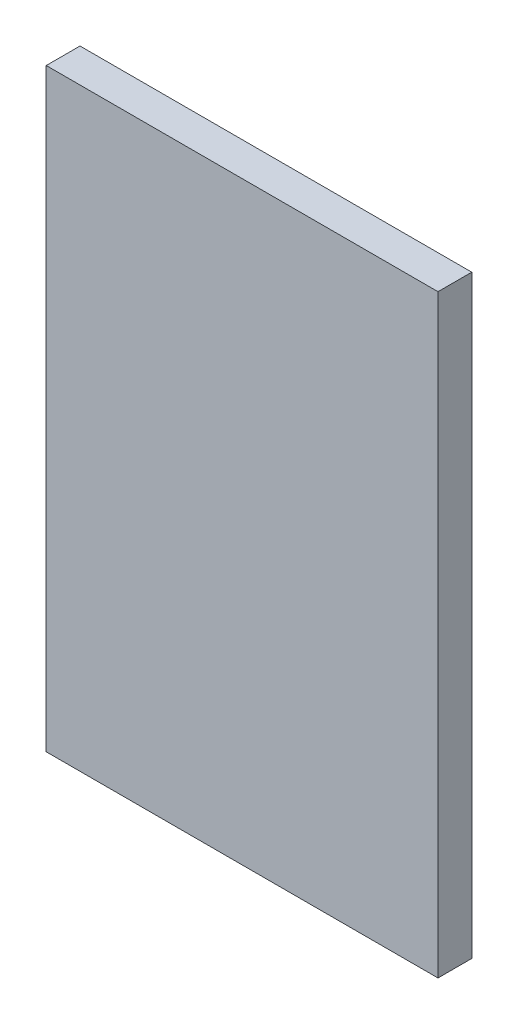
SolidWorks part; units mm, degrees
ref_plane "Front Plane" through (0, 0, 0) normal (1, 0, 0) x (0, 1, 0)
ref_plane "Top Plane" through (0, 0, 0) normal (0, 0, 1) x (0, 1, 0)
ref_plane "Right Plane" through (0, 0, 0) normal (0, 1, 0) x (-1, 0, 0)
sketch "Sketch1" plane through (0, 0, 0) normal (0, 0, 1) x (0, 1, 0)
  line L1 (0, 0) -> (88, 0)
  line L2 (0, 0) -> (0, 58)
  line L3 (0, 58) -> (88, 58)
  line L4 (88, 0) -> (88, 58)
extrude "Boss-Extrude1" add sketch "Sketch1" along normal blind 5
